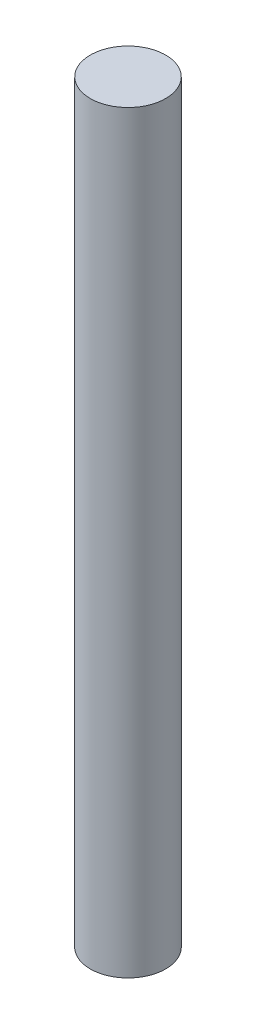
SolidWorks part; units mm, degrees
ref_plane "Front Plane" through (0, 0, 0) normal (0, 0, 1) x (1, 0, 0)
ref_plane "Top Plane" through (0, 0, 0) normal (0, 1, 0) x (1, 0, 0)
ref_plane "Right Plane" through (0, 0, 0) normal (1, 0, 0) x (0, 0, -1)
sketch "Sketch2" plane through (0, 0, 0) normal (0, 1, 0) x (1, 0, 0)
  circle A0 centre (0, 0) radius 0.508
  dimension "D1" = 1.016
extrude "Boss-Extrude1" add sketch "Sketch2" along normal blind 10.16
